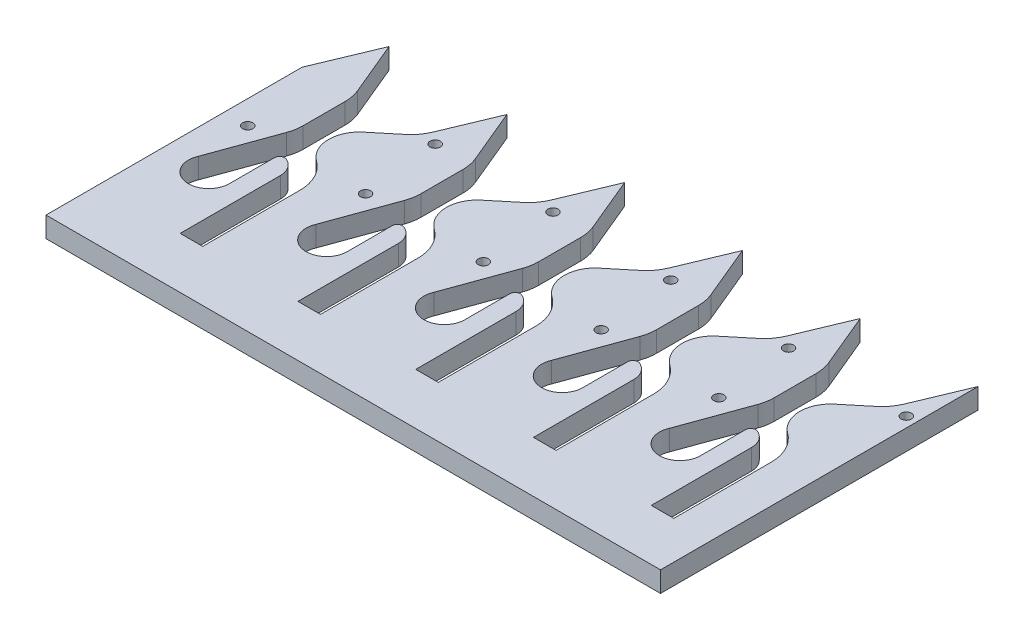
SolidWorks part; units mm, degrees
material "ABS"
ref_plane "Front Plane" through (0, 0, 0) normal (0, 0, 1) x (1, 0, 0)
ref_plane "Top Plane" through (0, 0, 0) normal (0, 1, 0) x (1, 0, 0)
ref_plane "Right Plane" through (0, 0, 0) normal (1, 0, 0) x (0, 0, -1)
sketch "Sketch1" plane through (0, 0, 0) normal (0, 1, 0) x (1, 0, 0)
  line L0 (-371.2073, 45) -> (137.2591, 45) construction
  line L1 (-371.2073, 155) -> (137.2591, 155) construction
  line L2 (-371.2073, 125) -> (137.2591, 125) construction
  line L5 (-371.2073, 25) -> (137.2591, 25) construction
  line L44 (137.2591, 0) -> (-371.2073, 0) construction
  line L45 (0, 0) -> (0, 226.1062) construction
  line L46 (-12.5, -27.5698) -> (-12.5, 226.1062) construction
  line L103 (0, 0) -> (-300, 0)
  line L105 (0, 0) -> (0, 155)
  line L106 (0, 155) -> (-12.5, 125)
  line L107 (-12.5, 125) -> (-27.5534, 112.5643)
  line L108 (-18.5, 86.0083) -> (-18.5, 25)
  line L109 (-18.5, 25) -> (-29.5, 25)
  line L110 (-57.5, 155) -> (-45, 125)
  line L111 (-29.5, 25) -> (-29.5, 74)
  line L112 (-38.5, 83) -> (-38.5, 58)
  line L113 (-57.5, 233.627) -> (-57.5, -20.049) construction
  line L114 (-45, 125) -> (-45, 97)
  line L115 (-45, 97) -> (-57.6652, 62)
  line L116 (-57.5, 155) -> (-70, 125)
  line L117 (-115, 155) -> (-102.5, 125)
  line L118 (-102.5, 125) -> (-102.5, 97)
  line L119 (-102.5, 97) -> (-115.1652, 62)
  line L120 (-96, 83) -> (-96, 58)
  line L121 (-87, 25) -> (-87, 74)
  line L122 (-76, 25) -> (-87, 25)
  line L123 (-76, 86.0083) -> (-76, 25)
  line L124 (-70, 125) -> (-85.0534, 112.5643)
  line L125 (-115, 155) -> (-127.5, 125)
  line L126 (-172.5, 155) -> (-160, 125)
  line L127 (-160, 125) -> (-160, 97)
  line L128 (-160, 97) -> (-172.6652, 62)
  line L129 (-153.5, 83) -> (-153.5, 58)
  line L130 (-144.5, 25) -> (-144.5, 74)
  line L131 (-133.5, 25) -> (-144.5, 25)
  line L132 (-133.5, 86.0083) -> (-133.5, 25)
  line L133 (-127.5, 125) -> (-142.5534, 112.5643)
  line L134 (-172.5, 155) -> (-185, 125)
  line L135 (-230, 155) -> (-217.5, 125)
  line L136 (-217.5, 125) -> (-217.5, 97)
  line L137 (-217.5, 97) -> (-230.1652, 62)
  line L138 (-211, 83) -> (-211, 58)
  line L139 (-202, 25) -> (-202, 74)
  line L140 (-191, 25) -> (-202, 25)
  line L141 (-191, 86.0083) -> (-191, 25)
  line L142 (-185, 125) -> (-200.0534, 112.5643)
  line L143 (-230, 155) -> (-242.5, 125)
  line L144 (-287.5, 155) -> (-275, 125)
  line L145 (-275, 125) -> (-275, 97)
  line L146 (-275, 97) -> (-287.6652, 62)
  line L147 (-268.5, 83) -> (-268.5, 58)
  line L148 (-259.5, 25) -> (-259.5, 74)
  line L149 (-248.5, 25) -> (-259.5, 25)
  line L150 (-248.5, 86.0083) -> (-248.5, 25)
  line L151 (-242.5, 125) -> (-257.5534, 112.5643)
  line L162 (-287.5, 155) -> (-300, 125)
  line L171 (-300, 0) -> (-300, 125)
  line L173 (-300, 125) -> (-315.0534, 112.5643) [skipped]
  line L174 (-306, 86.0083) -> (-306, 25) [skipped]
  line L175 (-332.5, 125) -> (-332.5, 97) [skipped]
  line L176 (-332.5, 97) -> (-345.1652, 62) [skipped]
  line L177 (-326, 83) -> (-326, 58) [skipped]
  line L178 (-317, 25) -> (-317, 74) [skipped]
  line L179 (-306, 25) -> (-317, 25) [skipped]
  line L180 (-345, 155) -> (-332.5, 125) [skipped]
  arc A0 (-27.5534, 112.5643) -> (-18.5, 86.0083) centre (-18, 101) ccw
  arc A1 (-29.5, 74) -> (-38.5, 83) centre (-38.5, 74) ccw
  arc A2 (-57.6652, 62) -> (-38.5, 58) centre (-48.5, 58) ccw
  arc A3 (-115.1652, 62) -> (-96, 58) centre (-106, 58) ccw
  arc A4 (-87, 74) -> (-96, 83) centre (-96, 74) ccw
  arc A5 (-85.0534, 112.5643) -> (-76, 86.0083) centre (-75.5, 101) ccw
  arc A6 (-172.6652, 62) -> (-153.5, 58) centre (-163.5, 58) ccw
  arc A7 (-144.5, 74) -> (-153.5, 83) centre (-153.5, 74) ccw
  arc A8 (-142.5534, 112.5643) -> (-133.5, 86.0083) centre (-133, 101) ccw
  arc A9 (-230.1652, 62) -> (-211, 58) centre (-221, 58) ccw
  arc A10 (-202, 74) -> (-211, 83) centre (-211, 74) ccw
  arc A11 (-200.0534, 112.5643) -> (-191, 86.0083) centre (-190.5, 101) ccw
  arc A12 (-287.6652, 62) -> (-268.5, 58) centre (-278.5, 58) ccw
  arc A13 (-259.5, 74) -> (-268.5, 83) centre (-268.5, 74) ccw
  arc A14 (-257.5534, 112.5643) -> (-248.5, 86.0083) centre (-248, 101) ccw
  arc A18 (-315.0534, 112.5643) -> (-306, 86.0083) centre (-305.5, 101) ccw [skipped]
  arc A19 (-345.1652, 62) -> (-326, 58) centre (-336, 58) ccw [skipped]
  arc A20 (-317, 74) -> (-326, 83) centre (-326, 74) ccw [skipped]
  circle A21 centre (-5, 125) radius 2.5
  circle A22 centre (-58.5, 87) radius 2.5
  circle A23 centre (-62.5, 125) radius 2.5
  circle A24 centre (-116, 87) radius 2.5
  circle A25 centre (-120, 125) radius 2.5
  circle A26 centre (-173.5, 87) radius 2.5
  circle A27 centre (-177.5, 125) radius 2.5
  circle A28 centre (-231, 87) radius 2.5
  circle A29 centre (-235, 125) radius 2.5
  circle A30 centre (-288.5, 87) radius 2.5
  dimension "D7" = 30
  dimension "D8" = 24
  dimension "D9" = 18
  dimension "D12" = 9
  dimension "D13" = 57.5
  dimension "D18" = 35
  dimension "D16" = 10
  dimension "D21" = 5
  dimension "D23" = 5
  dimension "D2" = 25
  dimension "D3" = 20
  dimension "D4" = 80
  dimension "D5" = 30
  dimension "D6" = 12.5
  dimension "D10" = 11
  dimension "D11" = 6
  dimension "D14" = 13
  dimension "D15" = 300
  dimension "D17" = 49
  dimension "D19" = 28
  dimension "D20" = 6
  dimension "D22" = 5
  dimension "D24" = 1
  dimension "D25" = 38
  dimension "D26" = 5
extrude "Boss-Extrude1" add sketch "Sketch1" along normal blind 10
fillet "Fillet1" radius 20 20 edges at (-45, 5, -125) (-102.5, 5, -125) (-160, 5, -125) (-217.5, 5, -125) (-275, 5, -125) (-45, 5, -97) (-102.5, 5, -97) (-160, 5, -97) (-217.5, 5, -97) (-275, 5, -97) (-12.5, 5, -125) (-70, 5, -125) (-127.5, 5, -125) (-185, 5, -125) (-242.5, 5, -125) (-18.5, 5, -86.0083) (-76, 5, -86.0083) (-133.5, 5, -86.0083) (-191, 5, -86.0083) (-248.5, 5, -86.0083)
fillet "Fillet2" radius 2.5 5 edges at (-38.5, 5, -83) (-96, 5, -83) (-153.5, 5, -83) (-211, 5, -83) (-268.5, 5, -83)
